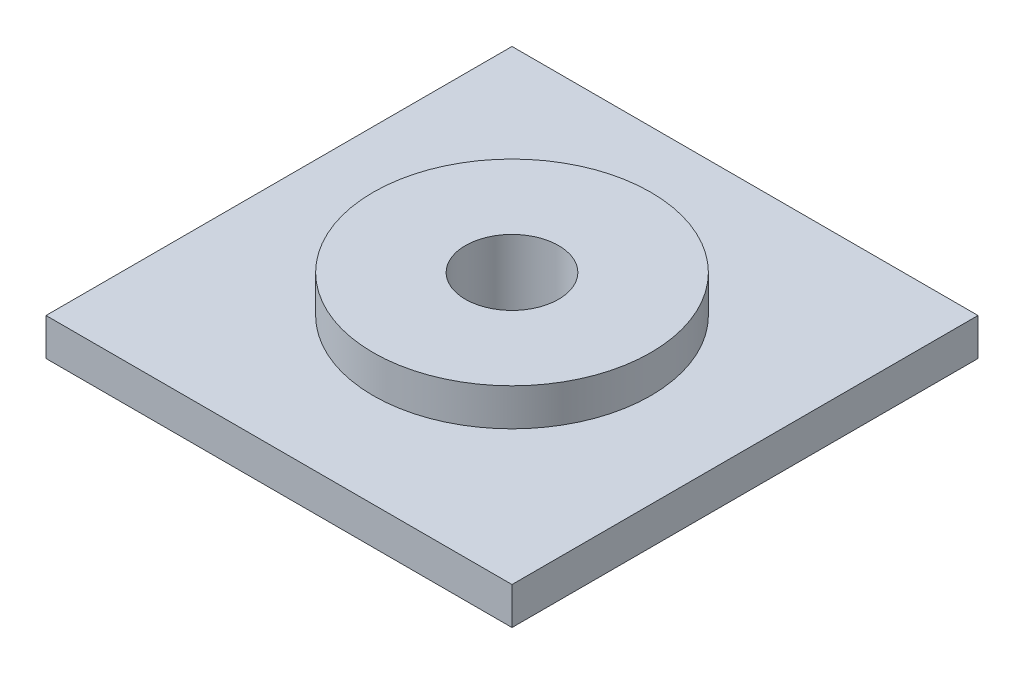
SolidWorks part; units mm, degrees
ref_plane "Front Plane" through (0, 0, 0) normal (0, 0, 1) x (1, 0, 0)
ref_plane "Top Plane" through (0, 0, 0) normal (0, 1, 0) x (1, 0, 0)
ref_plane "Right Plane" through (0, 0, 0) normal (1, 0, 0) x (0, 0, -1)
sketch "Sketch1" plane through (0, 0, 0) normal (0, 1, 0) x (1, 0, 0)
  line L1 (-12.5, -12.5) -> (12.5, -12.5)
  line L2 (-12.5, -12.5) -> (-12.5, 12.5)
  line L3 (-12.5, 12.5) -> (12.5, 12.5)
  line L4 (12.5, -12.5) -> (12.5, 12.5)
  line L5 (-12.5, -12.5) -> (12.5, 12.5) construction
  line L6 (-12.5, 12.5) -> (12.5, -12.5) construction
  point P0 (0, 0)
  dimension "D1" = 25
  dimension "D2" = 25
extrude "Boss-Extrude1" add sketch "Sketch1" along normal blind 2
sketch "Sketch2" plane through (0, 2, 0) normal (0, 1, 0) x (1, 0, 0)
  circle A0 centre (0, 0) radius 7.45
  dimension "D1" = 14.9
extrude "Boss-Extrude2" add sketch "Sketch2" along normal blind 2
sketch "Sketch3" plane through (0, 4, 0) normal (0, 1, 0) x (1, 0, 0)
  circle A0 centre (0, 0) radius 2.5
  dimension "D1" = 5
extrude "Cut-Extrude1" cut sketch "Sketch3" against normal through all
sketch "Sketch4" plane through (0, 0, 0) normal (0, 1, 0) x (1, 0, 0)
  line L0 (-12.5, 5) -> (12.5, 5) construction
  line L1 (-12.5, 12.5) -> (-12.5, -12.5) construction
  line L2 (12.5, -12.5) -> (12.5, 12.5) construction
  circle A0 centre (0, 0) radius 7.45 construction
  text T0 "<b>5mm</b>" font "Century Gothic" height 6
  dimension "D1" = 5
extrude "Cut-Extrude2" cut sketch "Sketch4" along normal blind 1
